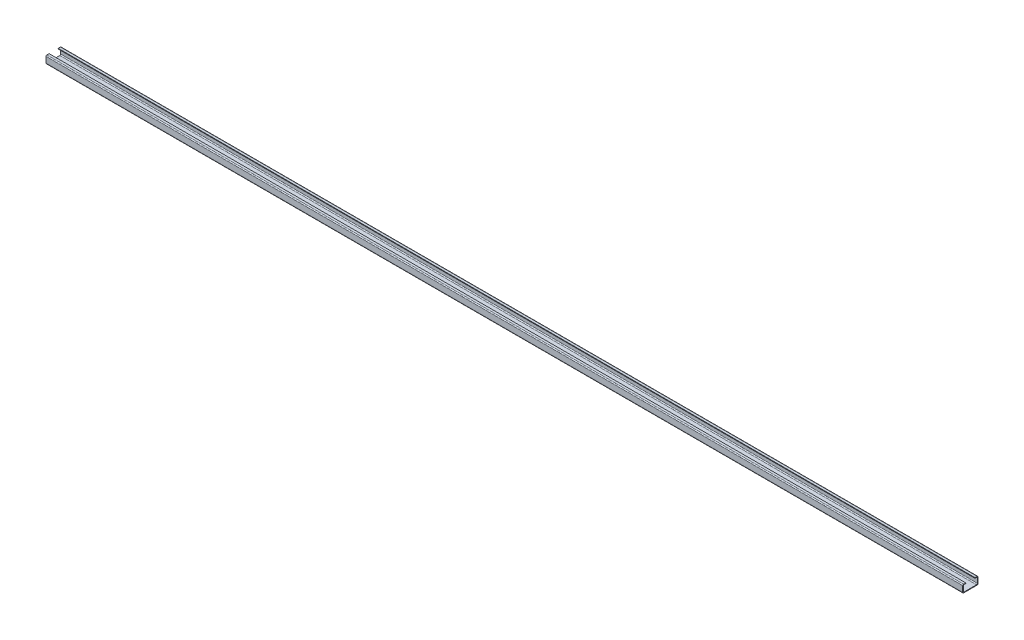
SolidWorks part; units mm, degrees
material "AISI 1045 Aço, trefilado"
ref_plane "Plano frontal" through (0, 0, 0) normal (0, 0, 1) x (1, 0, 0)
ref_plane "Plano superior" through (0, 0, 0) normal (0, 1, 0) x (1, 0, 0)
ref_plane "Plano direito" through (0, 0, 0) normal (1, 0, 0) x (0, 0, -1)
sketch "Esboço1" plane through (0, 0, 0) normal (1, 0, 0) x (0, 0, -1)
  line L0 (-46, 21) -> (-46, -21)
  line L1 (-50, 25) -> (-30, 25)
  line L2 (-50, 25) -> (-50, -25)
  line L3 (-50, -25) -> (50, -25)
  line L4 (50, 25) -> (50, -25)
  line L5 (-50, 25) -> (50, -25) construction
  line L6 (-50, -25) -> (50, 25) construction
  line L7 (-46, -21) -> (46, -21)
  line L8 (46, 21) -> (46, -21)
  line L9 (-46, 21) -> (-30, 21)
  line L10 (-30, 25) -> (-30, 21)
  line L13 (30, 25) -> (30, 21)
  line L14 (30, 21) -> (46, 21)
  line L15 (-46, 21) -> (46, 21) construction
  line L16 (30, 25) -> (50, 25)
  line L17 (-50, 25) -> (50, 25) construction
  point P0 (0, 0)
  dimension "D1" = 100
  dimension "D2" = 50
  dimension "D4" = 20
  dimension "D5" = 20
  dimension "D3" = 4
extrude "Ressalto-extrusão1" add sketch "Esboço1" along normal blind 6000
sketch "Esboço3" plane through (0, 25, 0) normal (0, 1, 0) x (1, 0, 0)
  line L0 (6000, -30) -> (6000, -50) construction
  line L1 (6000, 50) -> (6000, 30) construction
  line L2 (0, -30) -> (0, -50) construction
  line L3 (0, 50) -> (0, 30) construction
  line L4 (6000, -30) -> (6000, -50) construction
  line L5 (6000, 50) -> (6000, 30) construction
  line L6 (0, -30) -> (0, -50) construction
  line L7 (0, 50) -> (0, 30) construction
  line L8 (0, 30) -> (0, -30) construction
  line L9 (6000, 30) -> (6000, -30) construction
  line L10 (6000, 0) -> (0, 0) construction
  line L11 (3000, 0) -> (3000, 50) construction
  line L12 (6000, 50) -> (0, 50) construction
fillet "Filete1" radius 6 8 edges at (3000, 21, -46) (3000, 21, 46) (3000, 25, 50) (3000, 25, -50) (3000, -25, -50) (3000, -21, -46) (3000, -21, 46) (3000, -25, 50)
